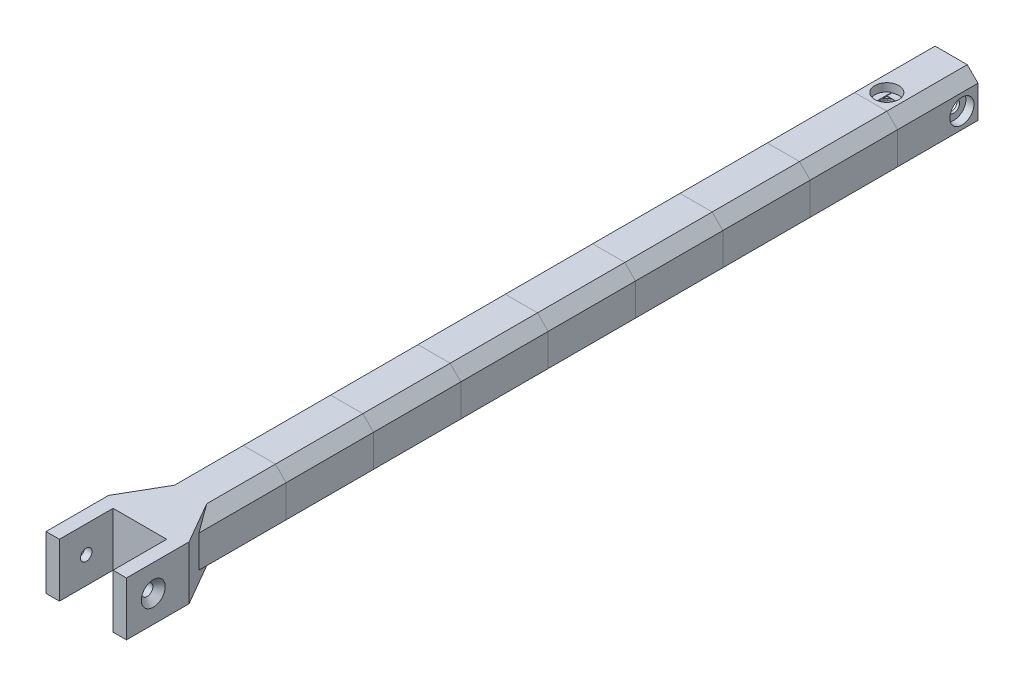
SolidWorks part; units mm, degrees
ref_plane "Front Plane" through (0, 0, 0) normal (0, 0, 1) x (1, 0, 0)
ref_plane "Top Plane" through (0, 0, 0) normal (0, 1, 0) x (1, 0, 0)
ref_plane "Right Plane" through (0, 0, 0) normal (1, 0, 0) x (0, 0, -1)
sketch "Sketch1" plane through (0, 0, 0) normal (0, 0, 1) x (1, 0, 0)
  line L1 (-10, -10) -> (10, -10)
  line L2 (-10, -10) -> (-10, 10)
  line L3 (-10, 10) -> (10, 10)
  line L4 (10, -10) -> (10, 10)
  line L5 (-10, -10) -> (10, 10) construction
  line L6 (-10, 10) -> (10, -10) construction
  point P0 (0, 0)
  dimension "D1" = 20
extrude "Boss-Extrude1" add sketch "Sketch1" along normal blind 302.5
sketch "Sketch2" plane through (0, 10, 0) normal (0, 1, 0) x (1, 0, 0)
  line L0 (0, -302.5) -> (0, -322.5) construction
  line L1 (10, -302.5) -> (-10, -302.5) construction
  line L2 (10, -302.5) -> (10, -322.5)
  line L3 (10, -322.5) -> (15, -322.5)
  line L4 (15, -322.5) -> (15, -299.1603)
  line L5 (15, -299.1603) -> (10, -290.5)
  line L6 (10, -302.5) -> (10, 0) construction
  line L7 (10, -290.5) -> (10, -302.5)
  line L8 (-10, -290.5) -> (-10, -302.5)
  line L9 (-15, -299.1603) -> (-10, -290.5)
  line L10 (-15, -322.5) -> (-15, -299.1603)
  line L11 (-10, -322.5) -> (-15, -322.5)
  line L12 (-10, -302.5) -> (-10, -322.5)
  point P10 (0, 0)
  dimension "D1" = 20
  dimension "D2" = 5
  dimension "D3" = 30
  dimension "D4" = 12
extrude "Boss-Extrude2" add sketch "Sketch2" against normal up to surface (20 mm away) up to face at (0, -10, 151.25)
sketch "Sketch3" plane through (15, 0, 0) normal (1, 0, 0) x (0, 0, -1)
  line L0 (-312.5, 10) -> (-312.5, -10) construction
  line L1 (-322.5, 10) -> (-299.1603, 10) construction
  line L2 (-299.1603, -10) -> (-322.5, -10) construction
  line L3 (-322.5, -10) -> (-322.5, 10) construction
  circle A0 centre (-312.5, 0) radius 2.15
  dimension "D2" = 4.3
  dimension "D1" = 10
extrude "Cut-Extrude1" cut sketch "Sketch3" against normal through all
sketch "Sketch4" plane through (0, 10, 0) normal (0, 1, 0) x (1, 0, 0)
  line L1 (-10, 0) -> (-6, 0)
  line L2 (-10, 0) -> (-10, -30)
  line L3 (-10, -30) -> (-6, -30)
  line L4 (-6, 0) -> (-6, -30)
  line L5 (10, 0) -> (6, 0)
  line L6 (10, 0) -> (10, -30)
  line L7 (10, -30) -> (6, -30)
  line L8 (6, 0) -> (6, -30)
  dimension "D1" = 30
  dimension "D2" = 12
extrude "Cut-Extrude2" cut sketch "Sketch4" against normal through all
chamfer "Chamfer1" distance 2.3 angle 45 2 edges at (-15, 0, 310.35) (15, 0, 310.35)
sketch "Sketch5" plane through (6, 0, 0) normal (1, 0, 0) x (0, 0, -1)
  line L1 (0, 10) -> (-15, 10)
  line L2 (0, 10) -> (0, 2)
  line L3 (0, 2) -> (-15, 2)
  line L4 (-15, 10) -> (-15, 2)
  line L5 (0, -10) -> (-30, -10) construction
  dimension "D1" = 12
  dimension "D2" = 15
extrude "Cut-Extrude3" cut sketch "Sketch5" against normal through all
sketch "Sketch6" plane through (0, 2, 0) normal (0, 1, 0) x (1, 0, 0)
  line L0 (-6, 0) -> (6, 0) construction
  circle A0 centre (0, -6) radius 3.2
  dimension "D1" = 6.4
  dimension "D2" = 6
extrude "Cut-Extrude4" cut sketch "Sketch6" against normal through all
sketch "Sketch7" plane through (6, 0, 0) normal (1, 0, 0) x (0, 0, -1)
  line L1 (-30, -10) -> (-30, 10) construction
  line L2 (-15, 10) -> (-30, 10) construction
  circle A0 centre (-24, 0) radius 3.2
  dimension "D1" = 6.4
  dimension "D2" = 6
  dimension "D3" = 10
extrude "Cut-Extrude5" cut sketch "Sketch7" against normal through all
sketch "Sketch10" plane through (0, 10, 0) normal (0, 1, 0) x (1, 0, 0)
  line L0 (10, -290.5) -> (10, -30) construction
  line L1 (-10, -30) -> (10, -30)
  line L2 (-10, -30) -> (-10, -62.5625)
  line L3 (-10, -62.5625) -> (10, -62.5625)
  line L4 (10, -30) -> (10, -62.5625)
  line L5 (-10, -290.5) -> (-10, -30) construction
  line L6 (10, -95.125) -> (-10, -95.125)
  line L7 (10, -95.125) -> (10, -127.6875)
  line L8 (10, -127.6875) -> (-10, -127.6875)
  line L9 (-10, -95.125) -> (-10, -127.6875)
  line L10 (10, -62.5625) -> (10, -95.125) construction
  line L11 (-10, -160.25) -> (10, -160.25)
  line L12 (-10, -160.25) -> (-10, -192.8125)
  line L13 (-10, -192.8125) -> (10, -192.8125)
  line L14 (10, -160.25) -> (10, -192.8125)
  line L15 (10, -225.375) -> (-10, -225.375)
  line L16 (10, -225.375) -> (10, -257.9375)
  line L17 (10, -257.9375) -> (-10, -257.9375)
  line L18 (-10, -225.375) -> (-10, -257.9375)
  line L19 (10, -127.6875) -> (10, -160.25) construction
  line L20 (10, -192.8125) -> (10, -225.375) construction
  line L21 (10, -257.9375) -> (10, -290.5) construction
extrude "Cut-Extrude7" cut sketch "Sketch10" against normal through all
sketch "Sketch11" plane through (0, 10, 0) normal (0, 1, 0) x (1, 0, 0)
  line L0 (-6, -30) -> (6, -30) construction
  line L1 (-10, -62.5625) -> (10, -62.5625)
  line L2 (-10, -62.5625) -> (-10, -30)
  line L3 (-10, -30) -> (10, -30)
  line L4 (10, -62.5625) -> (10, -30)
  line L5 (10, -95.125) -> (-10, -95.125)
  line L6 (10, -95.125) -> (10, -127.6875)
  line L7 (10, -127.6875) -> (-10, -127.6875)
  line L8 (-10, -95.125) -> (-10, -127.6875)
  line L9 (-10, -160.25) -> (10, -160.25)
  line L10 (-10, -160.25) -> (-10, -192.8125)
  line L11 (-10, -192.8125) -> (10, -192.8125)
  line L12 (10, -160.25) -> (10, -192.8125)
  line L13 (-10, -225.375) -> (10, -225.375)
  line L14 (-10, -225.375) -> (-10, -257.9375)
  line L15 (-10, -257.9375) -> (10, -257.9375)
  line L16 (10, -225.375) -> (10, -257.9375)
  line L17 (10, -95.125) -> (10, -62.5625) construction
extrude "Boss-Extrude3" add sketch "Sketch11" against normal up to surface (20 mm away) separate body up to face at (0, -10, 78.8437)
chamfer "Chamfer3" distance 4 angle 45 4 edges at (10, 10, 274.2187) (-10, 10, 274.2187) (-10, -10, 274.2187) (10, -10, 274.2187)
sketch "Sketch12" plane through (0, 0, 30) normal (0, 0, -1) x (-1, 0, 0)
  line L17 (-10, 10) -> (-6, 10)
  line L18 (-10, 10) -> (10, 10) construction
  line L19 (-6, 10) -> (-10, 6)
  line L20 (-10, -10) -> (-10, 10) construction
  line L21 (-10, 6) -> (-10, 10)
  line L22 (-10, -10) -> (-10, -6)
  line L23 (-10, -6) -> (-6, -10)
  line L24 (10, -10) -> (-10, -10) construction
  line L25 (-6, -10) -> (-10, -10)
  line L35 (6, 10) -> (10, 10)
  line L36 (6, 10) -> (15, 10) construction
  line L37 (10, 10) -> (10, 6)
  line L38 (10, 6) -> (6, 10)
  line L39 (10, -10) -> (10, -6)
  line L40 (10, -10) -> (10, 10) construction
  line L41 (10, -6) -> (6, -10)
  line L42 (6, -10) -> (10, -10)
  line L43 (10, -6) -> (10, 6) construction
  dimension "D1" = 4
extrude "Cut-Extrude8" cut sketch "Sketch12" against normal up to surface (227.9375 mm away) up to face at (0, 0, 257.9375)
sketch "Sketch13" plane through (6, 0, 0) normal (1, 0, 0) x (0, 0, -1)
  line L1 (-15, 10) -> (-30, 10)
  line L2 (-15, 10) -> (-15, 6)
  line L3 (-15, 6) -> (-30, 6)
  line L4 (-30, 10) -> (-30, 6)
extrude "Cut-Extrude9" cut sketch "Sketch13" against normal through all
sketch "Sketch14" plane through (0, 0, 30) normal (0, 0, -1) x (-1, 0, 0)
  line L0 (-6, -10) -> (-6, 6)
  line L1 (-6, 6) -> (6, 6)
  line L2 (6, 6) -> (6, -10)
  line L8 (6, 10) -> (-6, 10)
  line L9 (-6, 10) -> (-10, 6)
  line L10 (-10, 6) -> (-10, -6)
  line L11 (-10, -6) -> (-6, -10)
  line L12 (-6, -10) -> (6, -10)
  line L13 (6, -10) -> (10, -6)
  line L14 (10, -6) -> (10, 6)
  line L15 (10, 6) -> (6, 10)
  line L16 (6, 10) -> (-6, 10)
  line L17 (-6, 10) -> (-10, 6)
  line L18 (-10, 6) -> (-10, -6)
  line L19 (-10, -6) -> (-6, -10)
  line L20 (-6, -10) -> (6, -10) construction
  line L21 (6, -10) -> (10, -6)
  line L22 (10, -6) -> (10, 6)
  line L23 (10, 6) -> (6, 10)
  dimension "D1" = 0
sketch "Sketch15" plane through (0, 0, 0) normal (0, 0, -1) x (-1, 0, 0)
  line L1 (-6, 6) -> (6, 6)
  line L2 (-6, 6) -> (-6, -10)
  line L3 (-6, -10) -> (6, -10)
  line L4 (6, 6) -> (6, -10)
extrude "Cut-Extrude10" cut sketch "Sketch15" against normal up to surface (30 mm away) up to face at (0, 0, 30)
extrude "Boss-Extrude4" add sketch "Sketch14" along normal blind 30 separate body
sketch "Sketch16" plane through (0, 6, 0) normal (0, -1, 0) x (1, 0, 0)
  line L5 (6, 0) -> (6, 30) construction
  line L6 (-6, 30) -> (6, 30)
  line L7 (-6, 30) -> (-6, 15)
  line L8 (-6, 15) -> (6, 15)
  line L9 (6, 30) -> (6, 15)
  dimension "D1" = 15
extrude "Boss-Extrude5" add sketch "Sketch16" along normal offset from surface (4 mm away) 8 up to face at (0, 10, 46.2813)
sketch "Sketch17" plane through (0, 2, 0) normal (0, -1, 0) x (1, 0, 0)
  line L1 (6, 0) -> (-6, 0) construction
  circle A0 centre (0, 24) radius 2.15
  point P2 (0, 0)
  dimension "D1" = 4.3
  dimension "D2" = 24
extrude "Cut-Extrude11" cut sketch "Sketch17" against normal through all
sketch "Sketch18" plane through (10, 0, 0) normal (1, 0, 0) x (0, 0, -1)
  line L0 (0, 6) -> (0, -6) construction
  circle A0 centre (-6, 0) radius 2.15
  point P2 (0, 0)
  dimension "D1" = 6
  dimension "D2" = 4.3
extrude "Cut-Extrude12" cut sketch "Sketch18" against normal through all
sketch "Sketch19" plane through (10, 0, 0) normal (1, 0, 0) x (0, 0, -1)
  circle A0 centre (-6, 0) radius 4.5
  dimension "D1" = 9
extrude "Cut-Extrude13" cut sketch "Sketch19" against normal blind 3
sketch "Sketch20" plane through (0, 10, 0) normal (0, 1, 0) x (1, 0, 0)
  circle A0 centre (0, -24) radius 4.5
  dimension "D1" = 9
extrude "Cut-Extrude14" cut sketch "Sketch20" against normal blind 3
sketch "Sketch21" plane through (0, 7, 0) normal (0, 1, 0) x (1, 0, 0)
  line L2 (-2.15, -27.9532) -> (-2.15, -20.0468)
  line L4 (2.15, -27.9532) -> (2.15, -20.0468)
  line L5 (-2.15, -27.9532) -> (2.15, -20.0468) construction
  line L6 (-2.15, -20.0468) -> (2.15, -27.9532) construction
  circle A0 centre (0, -24) radius 4.5 construction
  circle A1 centre (0, -24) radius 4.5 construction
  arc A2 (2.15, -20.0468) -> (-2.15, -20.0468) centre (0, -24) ccw
  circle A3 centre (0, -24) radius 2.15 construction
  arc A4 (-2.15, -27.9532) -> (2.15, -27.9532) centre (0, -24) ccw
  point P0 (0, -24)
extrude "Cut-Extrude15" cut sketch "Sketch21" against normal blind 0.2
sketch "Sketch22" plane through (0, 6.8, 0) normal (0, 1, 0) x (1, 0, 0)
  line L0 (2.15, -27.9532) -> (2.15, -20.0468) construction
  line L1 (-2.15, -26.15) -> (2.15, -26.15)
  line L2 (-2.15, -26.15) -> (-2.15, -21.85)
  line L3 (-2.15, -21.85) -> (2.15, -21.85)
  line L4 (2.15, -26.15) -> (2.15, -21.85)
  line L5 (-2.15, -26.15) -> (2.15, -21.85) construction
  line L6 (-2.15, -21.85) -> (2.15, -26.15) construction
  point P0 (0, -24)
extrude "Cut-Extrude16" cut sketch "Sketch22" against normal blind 0.2
